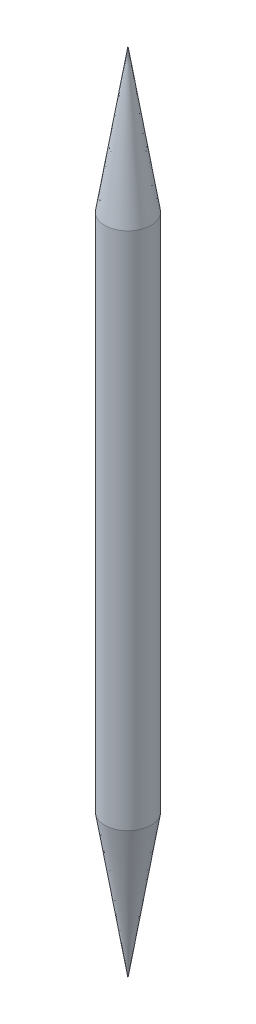
SolidWorks part; units mm, degrees
ref_plane "Front Plane" through (0, 0, 0) normal (0, 0, 1) x (1, 0, 0)
ref_plane "Top Plane" through (0, 0, 0) normal (0, 1, 0) x (1, 0, 0)
ref_plane "Right Plane" through (0, 0, 0) normal (1, 0, 0) x (0, 0, -1)
sketch "Sketch1" plane through (0, 0, 0) normal (0, 1, 0) x (1, 0, 0)
  circle A0 centre (0, 0) radius 44.45
extrude "Boss-Extrude1" add sketch "Sketch1" along normal blind 1000
sketch "Sketch3" plane through (0, 0, 0) normal (0, 0, 1) x (1, 0, 0)
  line L0 (0, 1000) -> (0, 1276.86)
  line L1 (44.45, 1000) -> (-44.45, 1000) construction
  line L2 (0, 1276.86) -> (-44.45, 1000)
  line L3 (-44.45, 1000) -> (0, 1000)
revolve "Revolve3" add sketch "Sketch3" angle 360 about L0
sketch "Sketch4" plane through (0, 0, 0) normal (0, 0, 1) x (1, 0, 0)
  line L0 (0, 0) -> (0, -276.86)
  line L1 (0, -276.86) -> (-44.45, 0)
  line L2 (-44.45, 0) -> (44.45, 0) construction
  line L3 (-44.45, 0) -> (0, 0)
revolve "Revolve4" add sketch "Sketch4" angle 360 about L0
